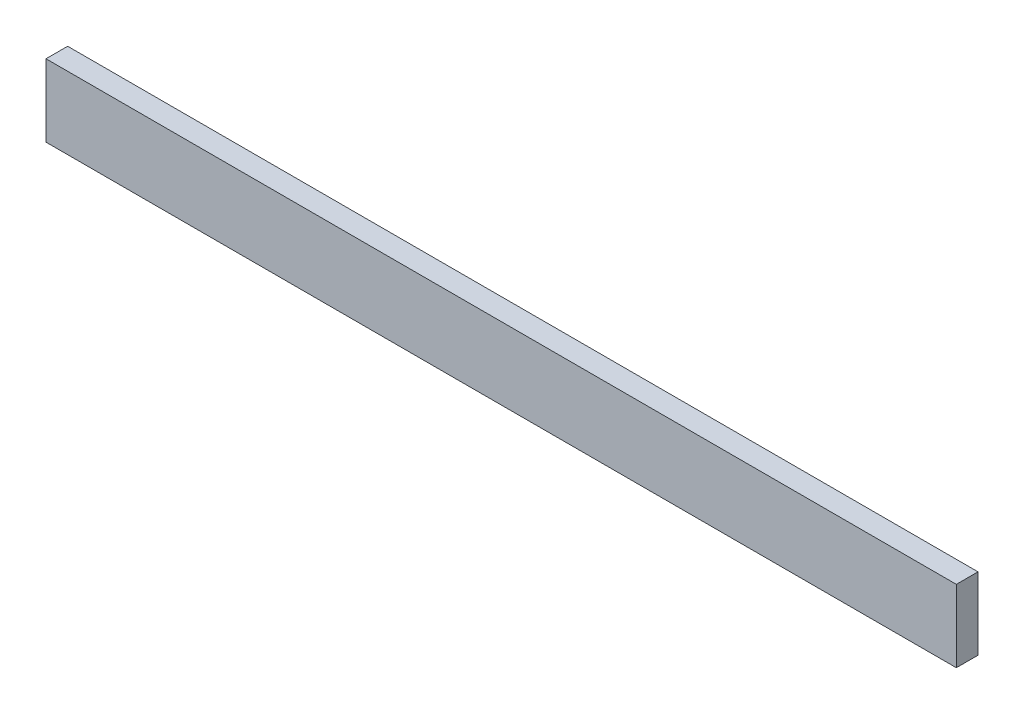
SolidWorks part; units mm, degrees
ref_plane "Front Plane" through (0, 0, 0) normal (0, 0, 1) x (1, 0, 0)
ref_plane "Top Plane" through (0, 0, 0) normal (0, 1, 0) x (1, 0, 0)
ref_plane "Right Plane" through (0, 0, 0) normal (1, 0, 0) x (0, 0, -1)
sketch "Sketch1" plane through (0, 0, 0) normal (0, 0, 1) x (1, 0, 0)
  line L1 (-80.01, 6.35) -> (80.01, 6.35)
  line L2 (-80.01, 6.35) -> (-80.01, -6.35)
  line L3 (-80.01, -6.35) -> (80.01, -6.35)
  line L4 (80.01, 6.35) -> (80.01, -6.35)
  line L5 (-80.01, 6.35) -> (80.01, -6.35) construction
  line L6 (-80.01, -6.35) -> (80.01, 6.35) construction
  point P0 (0, 0)
  dimension "D1" = 160.02
  dimension "D2" = 12.7
extrude "Boss-Extrude1" add sketch "Sketch1" along normal blind 3.81
